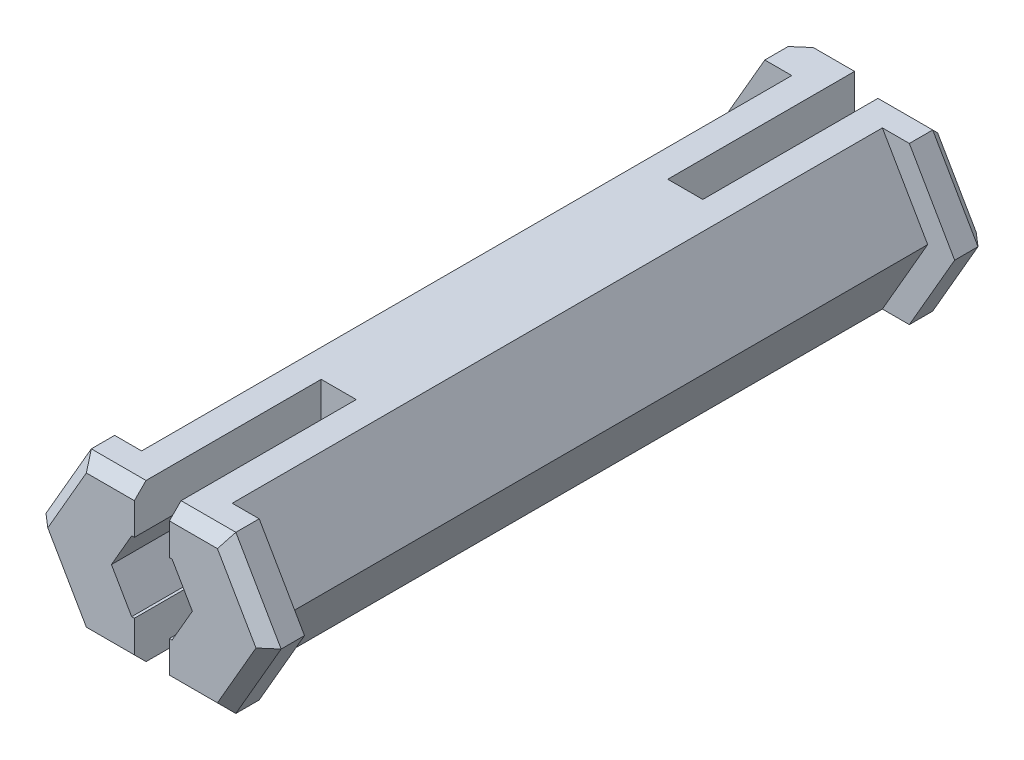
SolidWorks part; units mm, degrees
ref_plane "Plan de face" through (0, 0, 0) normal (1, 0, 0) x (0, 1, 0)
ref_plane "Plan de dessus" through (0, 0, 0) normal (0, 0, 1) x (0, 1, 0)
ref_plane "Plan de droite" through (0, 0, 0) normal (0, 1, 0) x (-1, 0, 0)
sketch "Esquisse1" plane through (0, 0, 0) normal (0, 0, 1) x (0, 1, 0)
  line L1 (0, 3.8798) -> (-3.36, 1.9399)
  line L2 (-3.36, 1.9399) -> (-3.36, -1.9399)
  line L3 (-3.36, -1.9399) -> (0, -3.8798)
  line L4 (0, -3.8798) -> (3.36, -1.9399)
  line L5 (3.36, -1.9399) -> (3.36, 1.9399)
  line L6 (3.36, 1.9399) -> (0, 3.8798)
  circle A0 centre (0, 0) radius 3.36 construction
  dimension "D1" = 6.72
extrude "Boss.-Extru.1" add sketch "Esquisse1" along normal mid plane 27.84
sketch "Esquisse2" plane through (0, 0, 13.92) normal (0, 0, 1) x (1, 0, 0)
  line L6 (-3.0946, 3.36) -> (3.0946, 3.36)
  line L7 (1.9399, 3.36) -> (-1.9399, 3.36) construction
  line L8 (-3.0946, -3.36) -> (3.0946, -3.36)
  line L9 (-1.9399, -3.36) -> (1.9399, -3.36) construction
  line L12 (-2.5172, 4.36) -> (-5.0345, 0)
  line L13 (-5.0345, 0) -> (-2.5172, -4.36)
  line L14 (-2.5172, -4.36) -> (2.5172, -4.36)
  line L15 (2.5172, -4.36) -> (5.0345, 0)
  line L16 (5.0345, 0) -> (2.5172, 4.36)
  line L17 (2.5172, 4.36) -> (-2.5172, 4.36)
  line L18 (-2.5172, 4.36) -> (-5.0345, 0)
  line L19 (-5.0345, 0) -> (-2.5172, -4.36)
  line L20 (-2.5172, -4.36) -> (2.5172, -4.36)
  line L21 (2.5172, -4.36) -> (5.0345, 0)
  line L22 (5.0345, 0) -> (2.5172, 4.36)
  line L23 (2.5172, 4.36) -> (-2.5172, 4.36)
  line M7 (-1.9399, 3.36) -> (-3.8798, 0)
  line M8 (-3.8798, 0) -> (-1.9399, -3.36)
  line M9 (-1.9399, -3.36) -> (1.9399, -3.36)
  line M10 (1.9399, -3.36) -> (3.8798, 0)
  line M11 (3.8798, 0) -> (1.9399, 3.36)
  line M12 (1.9399, 3.36) -> (-1.9399, 3.36)
  dimension "D1" = 1
extrude "Boss.-Extru.2" add sketch "Esquisse2" along normal blind 1.5 contours L18 L19 L8 L6 M8 M7 | L21 L22 L6 L8 M11 M10 | M12 M7 M8 M9 M10 M11
sketch "Esquisse4" plane through (0, 0, 15.42) normal (0, 0, 1) x (1, 0, 0)
  line L1 (-1.7321, 0) -> (-0.866, -1.5)
  line L2 (-0.866, -1.5) -> (0.866, -1.5)
  line L3 (0.866, -1.5) -> (1.7321, 0)
  line L4 (1.7321, 0) -> (0.866, 1.5)
  line L5 (0.866, 1.5) -> (-0.866, 1.5)
  line L6 (-0.866, 1.5) -> (-1.7321, 0)
  line L7 (-0.75, -4.2153) -> (0.75, -4.2153)
  line L8 (-0.75, -4.2153) -> (-0.75, 4.2153)
  line L9 (-0.75, 4.2153) -> (0.75, 4.2153)
  line L10 (0.75, -4.2153) -> (0.75, 4.2153)
  line L11 (-0.75, -4.2153) -> (0.75, 4.2153) construction
  line L12 (-0.75, 4.2153) -> (0.75, -4.2153) construction
  circle A0 centre (0, 0) radius 1.5 construction
  line M7 (-3.0946, -3.36) -> (3.0946, -3.36)
  line M10 (3.0946, 3.36) -> (-3.0946, 3.36)
  dimension "D1" = 3
  dimension "D2" = 1.5
extrude "Enlèv. mat.-Extru.1" cut sketch "Esquisse4" against normal blind 8 contours L10 L9 L8 M10 | L5 L10 L8 M10 | L2 L10 L5 L8 | L10 L2 L8 M7 | L10 L2 L3 L4 L5 | L2 L8 L5 L6 L1
mirror "Symétrie2" about plane through (0, 0, 0) normal (0, 0, 1) of "Boss.-Extru.2", "Enlèv. mat.-Extru.1"
chamfer "Chanfrein1" distance 0.5 angle 45 12 edges at (-1.9223, 3.36, 15.42) (-1.9223, -3.36, 15.42) (4.0645, -1.68, 15.42) (4.0645, 1.68, 15.42) (-4.0645, 1.68, 15.42) (-4.0645, -1.68, 15.42) (1.9223, -3.36, 15.42) (1.9223, 3.36, 15.42) (-4.0645, -1.68, -15.42) (-4.0645, 1.68, -15.42) (4.0645, 1.68, -15.42) (4.0645, -1.68, -15.42)
